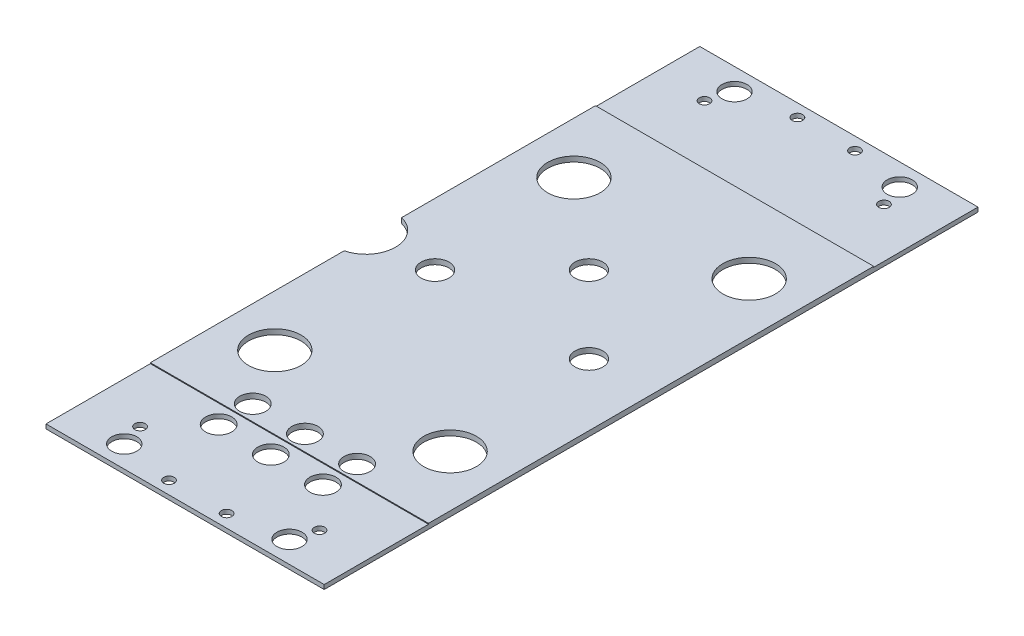
SolidWorks part; units mm, degrees
ref_plane "Front Plane" through (0, 0, 0) normal (0, 0, 1) x (1, 0, 0)
ref_plane "Top Plane" through (0, 0, 0) normal (0, 1, 0) x (1, 0, 0)
ref_plane "Right Plane" through (0, 0, 0) normal (1, 0, 0) x (0, 0, -1)
sketch "Croquis2" plane through (0, 0, 0) normal (0, 1, 0) x (1, 0, 0)
  line L1 (0, 0) -> (80, 0)
  line L2 (0, 0) -> (0, 128)
  line L3 (0, 128) -> (80, 128)
  line L4 (80, 0) -> (80, 128)
  dimension "D1" = 80
  dimension "D2" = 128
extrude "Saliente-Extruir1" add sketch "Croquis2" along normal blind 1.5
sketch "Croquis1" plane through (0, 0, 0) normal (0, -1, 0) x (1, 0, 0)
  line L0 (80, -64) -> (0, -64) construction
  line L1 (0, 0) -> (80, 0)
  line L2 (0, 0) -> (0, 30)
  line L3 (0, 30) -> (80, 30)
  line L4 (80, 0) -> (80, 30)
  line L5 (80, 0) -> (80, -128) construction
  line L6 (0, -128) -> (0, 0) construction
  line L7 (80, -128) -> (80, -158)
  line L8 (0, -158) -> (80, -158)
  line L9 (0, -128) -> (0, -158)
  line L10 (0, -128) -> (80, -128)
  dimension "D1" = 80
  dimension "D2" = 30
extrude "Saliente-Extruir2" add sketch "Croquis1" against normal blind 1.25
sketch "Croquis7" plane through (0, 0, 0) normal (0, 1, 0) x (1, 0, 0)
  line L0 (0, 64) -> (80, 64) construction
  line L1 (7.5, -12.25) -> (72.5, -12.25) construction
  line L2 (7.5, -12.25) -> (7.5, -30) construction
  line L3 (7.5, -30) -> (72.5, -30) construction
  line L4 (72.5, -12.25) -> (72.5, -30) construction
  line L5 (0, -30) -> (80, -30) construction
  line L6 (0, 128) -> (0, 0) construction
  line L7 (80, 0) -> (80, 128) construction
  line L8 (72.5, 140.25) -> (72.5, 158) construction
  line L9 (7.5, 140.25) -> (7.5, 158) construction
  line L10 (7.5, 140.25) -> (72.5, 140.25) construction
  point P8 (40, -30)
  point P12 (40, -30)
  dimension "D1" = 65
  dimension "D2" = 17.75
sketch "Croquis9" plane through (0, 0, 0) normal (0, 1, 0) x (1, 0, 0)
  line L0 (0, 0) -> (80, 0) construction
  line L1 (80, 0) -> (80, 128) construction
  line L2 (0, 128) -> (0, 0) construction
  line L3 (80, -30) -> (0, -30) construction
  dimension "D1" = 30
sketch "Croquis6" plane through (0, 0, 0) normal (0, -1, 0) x (1, 0, 0)
  line L0 (21.2, 5.3) -> (58.7, 5.3) construction
  line L2 (80, 0) -> (80, 30) construction
  circle A0 centre (24.95, 5.3) radius 3.75
  circle A1 centre (54.95, 5.3) radius 3.75
  circle A2 centre (39.95, 5.3) radius 3.75
  dimension "D2" = 7.5
  dimension "D3" = 7.5
  dimension "D4" = 7.5
  dimension "D1" = 37.5
  dimension "D5" = 5.3
  dimension "D6" = 21.3
  dimension "D7" = 24.7
extrude "Cortar-Extruir1" cut sketch "Croquis6" against normal blind 5.25
sketch "Croquis8" plane through (0, 0, 0) normal (0, 1, 0) x (1, 0, 0)
  circle A0 centre (24.95, 4.5) radius 3.75
  circle A1 centre (39.95, 4.5) radius 3.75
  circle A2 centre (54.95, 4.5) radius 3.75
  dimension "D1" = 7.5
  dimension "D2" = 4.5
extrude "Cortar-Extruir2" cut sketch "Croquis8" against normal blind 10 and the other way blind 10
sketch "Croquis10" plane through (0, 0, 0) normal (0, 1, 0) x (1, 0, 0)
  line L0 (0, 0) -> (80, 0) construction
  line L1 (80, 0) -> (80, 128) construction
  line L2 (40, 158) -> (40, -30) construction
  line L3 (0, 158) -> (80, 158) construction
  line L4 (7.5, -30) -> (72.5, -30) construction
  line L5 (72.5, -12.25) -> (72.5, -30) construction
  line L6 (0, 64) -> (80, 64) construction
  line L7 (0, 128) -> (0, 0) construction
  circle A0 centre (65.2, 21) radius 7.565
  circle A1 centre (14.8, 21) radius 7.565
  circle A2 centre (65.8, -17.15) radius 1.5
  circle A3 centre (63.75, -23.74) radius 3.6
  circle A4 centre (48.28, -26.35) radius 1.5
  circle A5 centre (31.72, -26.35) radius 1.5
  circle A6 centre (16.25, -23.74) radius 3.6
  circle A7 centre (14.2, -17.15) radius 1.5
  circle A8 centre (17.87, 64) radius 4
  circle A9 centre (40, 64) radius 27.25 construction
  circle A10 centre (40, 86.125) radius 4
  circle A11 centre (40, 64) radius 17 construction
  circle A12 centre (62.13, 64) radius 4
  circle A13 centre (65.8, 145.15) radius 1.5
  circle A14 centre (63.75, 151.74) radius 3.6
  circle A15 centre (48.28, 154.35) radius 1.5
  circle A16 centre (14.2, 145.15) radius 1.5
  circle A17 centre (31.72, 154.35) radius 1.5
  circle A18 centre (16.25, 151.74) radius 3.6
  circle A19 centre (65.2, 107) radius 7.565
  circle A20 centre (14.8, 107) radius 7.565
  circle A21 centre (-2, 64) radius 8.5
  dimension "D1" = 15.13
  dimension "D4" = 3
  dimension "D5" = 7.2
  dimension "D6" = 3
  dimension "D7" = 3.65
  dimension "D9" = 8.75
  dimension "D10" = 6.26
  dimension "D13" = 8
  dimension "D14" = 54.5
  dimension "D15" = 8
  dimension "D16" = 34
  dimension "D17" = 10.25
  dimension "D18" = 22.125
  dimension "D20" = 17
  dimension "D2" = 21
  dimension "D3" = 14.8
  dimension "D8" = 24.22
  dimension "D11" = 6.7
  dimension "D12" = 4.9
  dimension "D19" = 22.13
  dimension "D21" = 2
extrude "Cortar-Extruir4" cut sketch "Croquis10" along normal through all
